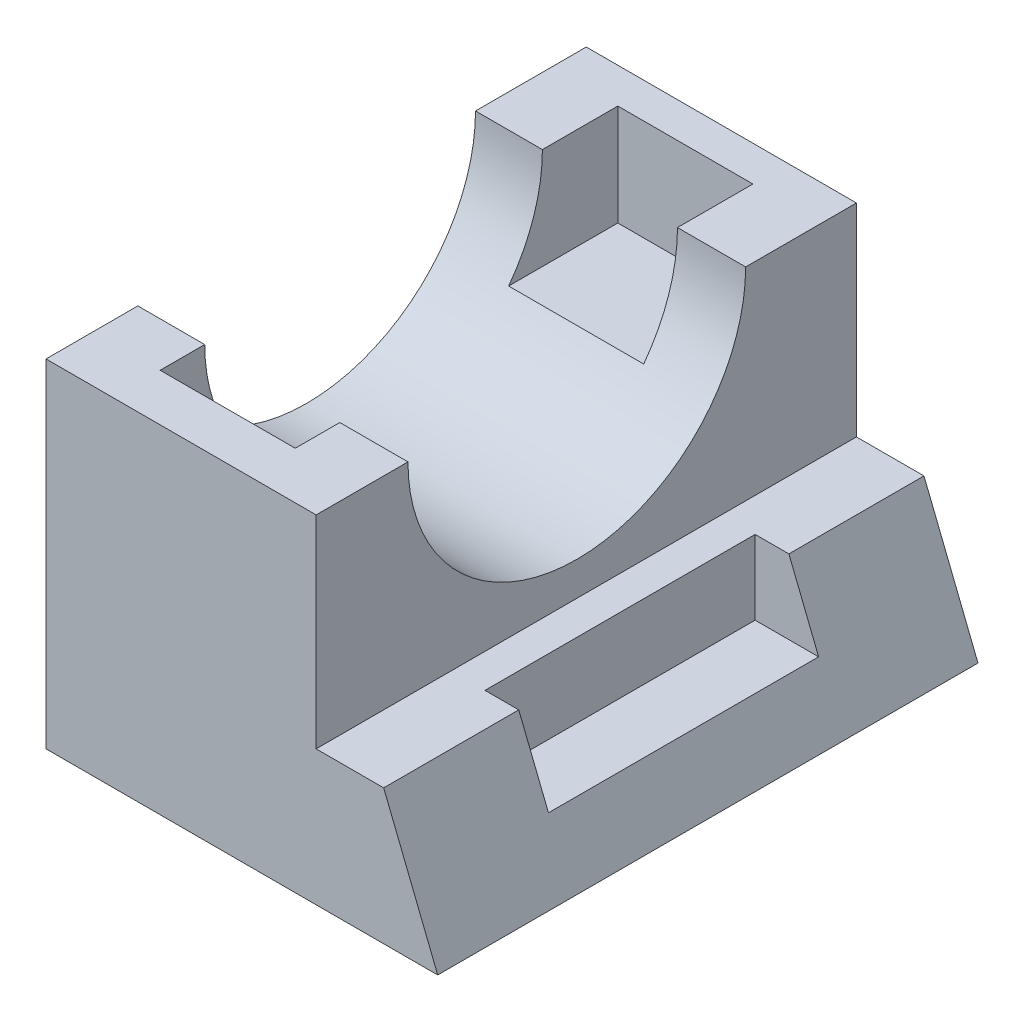
SolidWorks part; units mm, degrees
ref_plane "Front Plane" through (0, 0, 0) normal (0, 0, 1) x (1, 0, 0)
ref_plane "Top Plane" through (0, 0, 0) normal (0, 1, 0) x (1, 0, 0)
ref_plane "Right Plane" through (0, 0, 0) normal (1, 0, 0) x (0, 0, -1)
sketch "Sketch1" plane through (0, 0, 0) normal (0, 0, 1) x (1, 0, 0)
  line L0 (0, 50) -> (0, 0)
  line L1 (0, 0) -> (58, 0)
  line L2 (58, 0) -> (50, 20)
  line L3 (50, 20) -> (40, 20)
  line L4 (40, 20) -> (40, 50)
  line L5 (40, 50) -> (0, 50)
  dimension "D1" = 50
  dimension "D2" = 40
  dimension "D3" = 58
  dimension "D4" = 10
  dimension "D5" = 30
extrude "Boss-Extrude1" add sketch "Sketch1" along normal blind 80
sketch "Sketch2" plane through (0, 0, 0) normal (-1, 0, 0) x (0, 0, 1)
  line L0 (80, 50) -> (0, 50) construction
  line L1 (66.4026, 50) -> (16.4026, 50)
  arc A0 (66.4026, 50) -> (16.4026, 50) centre (41.4026, 50) cw
  dimension "D1" = 25
extrude "Cut-Extrude1" cut sketch "Sketch2" against normal blind 80
sketch "Sketch3" plane through (0, 50, 0) normal (0, 1, 0) x (1, 0, 0)
  line L0 (40, -80) -> (0, -80) construction
  line L1 (29.9053, -5.2345) -> (9.9053, -5.2345)
  line L2 (29.9053, -5.2345) -> (29.9053, -73)
  line L3 (29.9053, -73) -> (9.9053, -73)
  line L4 (9.9053, -5.2345) -> (9.9053, -73)
  line L5 (29.9053, -5.2345) -> (9.9053, -73) construction
  line L6 (29.9053, -73) -> (9.9053, -5.2345) construction
  point P4 (19.9053, -39.1172)
  dimension "D1" = 20
  dimension "D2" = 67.7655
  dimension "D3" = 7
extrude "Cut-Extrude2" cut sketch "Sketch3" against normal blind 15
sketch "Sketch6" plane through (0, 20, 0) normal (0, 1, 0) x (1, 0, 0)
  line L0 (40, -80) -> (40, 0) construction
  line L1 (45, -20) -> (55, -20)
  line L2 (45, -20) -> (45, -60)
  line L3 (45, -60) -> (55, -60)
  line L4 (55, -20) -> (55, -60)
  line L5 (45, -20) -> (55, -60) construction
  line L6 (45, -60) -> (55, -20) construction
  line L7 (50, 0) -> (40, 0) construction
  point P4 (50, -40)
  point P7 (40, -40)
  point P8 (50, -20)
  point P10 (-21.838, 18.7938)
  dimension "D1" = 5
  dimension "D2" = 5
  dimension "D3" = 40
  dimension "D4" = 20
extrude "Cut-Extrude4" cut sketch "Sketch6" against normal blind 11
